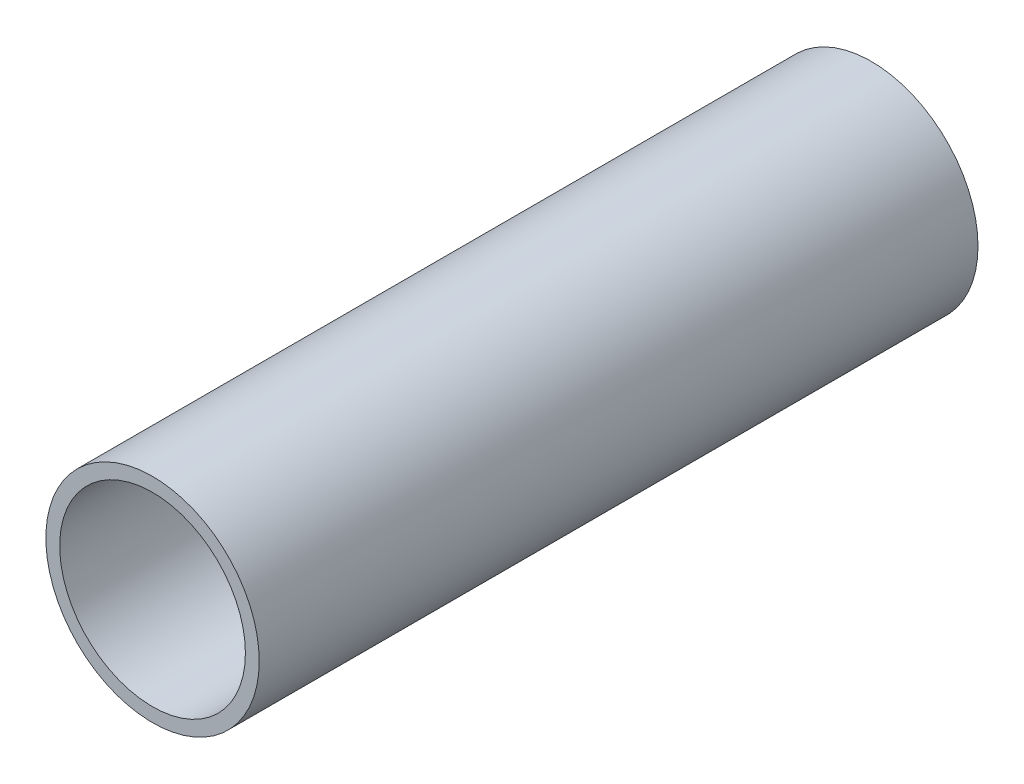
SolidWorks part; units mm, degrees
ref_plane "Front Plane" through (0, 0, 0) normal (0, 0, 1) x (1, 0, 0)
ref_plane "Top Plane" through (0, 0, 0) normal (0, 1, 0) x (1, 0, 0)
ref_plane "Right Plane" through (0, 0, 0) normal (1, 0, 0) x (0, 0, -1)
sketch "Sketch1" plane through (0, 0, 0) normal (0, 0, 1) x (1, 0, 0)
  circle A0 centre (0, 0) radius 30.1625
  circle A1 centre (0, 0) radius 26.2509
  dimension "D1" = 60.325
  dimension "D2" = 3.9116
extrude "Boss-Extrude1" add sketch "Sketch1" along normal blind 203.2
